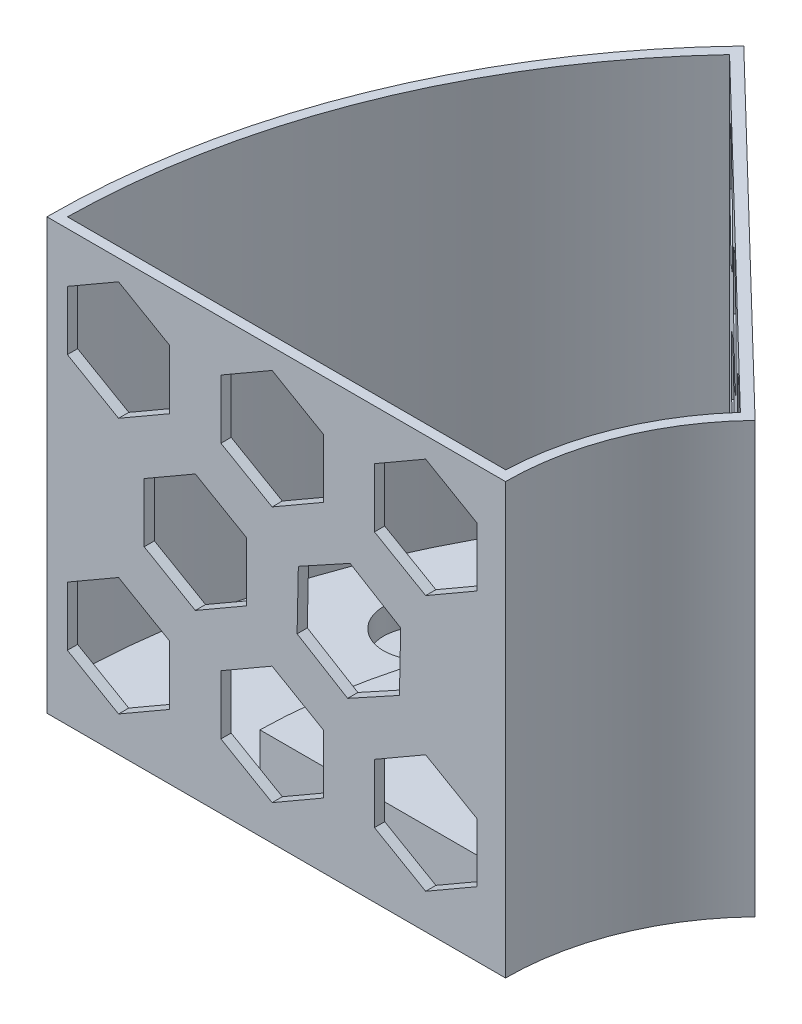
SolidWorks part; units mm, degrees
ref_plane "Alzado" through (0, 0, 0) normal (0, 0, 1) x (1, 0, 0)
ref_plane "Planta" through (0, 0, 0) normal (0, 1, 0) x (1, 0, 0)
ref_plane "Vista lateral" through (0, 0, 0) normal (1, 0, 0) x (0, 0, -1)
sketch "Croquis1" plane through (0, 0, 0) normal (0, 1, 0) x (1, 0, 0)
  line L0 (0, 0) -> (-75, 0) construction
  line L1 (0, 0) -> (-50.2099, 48.4872) construction
  line L2 (-25, 0) -> (-69.8, 0)
  line L4 (-50.2099, 48.4872) -> (-17.9835, 17.3665)
  circle A0 centre (0, 0) radius 75 construction
  circle A1 centre (0, 0) radius 69.8 construction
  circle A2 centre (0, 0) radius 25 construction
  arc A3 (-25, 0) -> (-17.9835, 17.3665) centre (0, 0) cw
  arc A4 (-69.8, 0) -> (-50.2099, 48.4872) centre (0, 0) cw
  dimension "D1" = 150
  dimension "D2" = 5.2
  dimension "D3" = 50
  dimension "D4" = 44
extrude "Saliente-Extruir1" add sketch "Croquis1" along normal blind 40
shell "Vaciado1" thickness 1
sketch "Croquis4" plane through (0, 0, 0) normal (0, -1, 0) x (1, 0, 0)
  line L0 (-25, 0) -> (-69.8, 0)
  line L1 (-17.9835, -17.3665) -> (-50.2099, -48.4872)
  arc A0 (-69.8, 0) -> (-50.2099, -48.4872) centre (0, 0) ccw
  arc A1 (-25, 0) -> (-17.9835, -17.3665) centre (0, 0) ccw
extrude "Saliente-Extruir3" add sketch "Croquis4" along normal blind 2
sketch "Croquis5" plane through (0, 1, 0) normal (0, 1, 0) x (1, 0, 0)
  line L0 (0, 0) -> (-64.7174, 26.1475) construction
  arc A1 (-50.2099, 48.4872) -> (-69.8, 0) centre (0, 0) ccw construction
  circle A2 centre (-55.631, 22.4764) radius 3.75
  dimension "D1" = 7.5
  dimension "D2" = 60
extrude "Cortar-Extruir2" cut sketch "Croquis5" against normal blind 2.5
sketch "Croquis6" plane through (0, 1, 0) normal (0, 1, 0) x (1, 0, 0)
  line L1 (-25, 0) -> (-50, 0)
  line L3 (-17.9835, 17.3665) -> (-35.967, 34.7329)
  line L4 (-17.9835, 17.3665) -> (-50.2099, 48.4872) construction
  circle A0 centre (0, 0) radius 50 construction
  arc A1 (-25, 0) -> (-17.9835, 17.3665) centre (0, 0) cw
  arc A3 (-50, 0) -> (-35.967, 34.7329) centre (0, 0) cw
  dimension "D1" = 100
extrude "Saliente-Extruir5" add sketch "Croquis6" along normal blind 5
sketch "Croquis2" plane through (0, -2, 0) normal (0, 1, 0) x (1, 0, 0)
  line L0 (-39.7289, 27.8185) -> (-29.899, 20.9355)
  line L1 (-47.9029, 7.5871) -> (-36.0506, 5.7099)
  line L2 (-17.9835, 17.3665) -> (-50.2099, 48.4872) construction
  circle A0 centre (0, 0) radius 36.5 construction
  circle A1 centre (0, 0) radius 48.5 construction
  arc A2 (-36.0506, 5.7099) -> (-29.899, 20.9355) centre (0, 0) cw
  arc A3 (-47.9029, 7.5871) -> (-39.7289, 27.8185) centre (0, 0) cw
  dimension "D1" = 73
  dimension "D2" = 97
  dimension "D3" = 9
  dimension "D4" = 26
extrude "Cortar-Extruir3" cut sketch "Croquis2" along normal blind 6
sketch "Croquis7" plane through (0, 0, 0) normal (0, 0, 1) x (1, 0, 0)
  line L0 (-69.8, 40) -> (-69.8, -2) construction
  line L1 (-62.8, 38) -> (-67.8, 35.1132)
  line L2 (-67.8, 35.1132) -> (-67.8, 29.3397)
  line L3 (-67.8, 29.3397) -> (-62.8, 26.453)
  line L4 (-62.8, 26.453) -> (-57.8, 29.3397)
  line L5 (-57.8, 29.3397) -> (-57.8, 35.1132)
  line L6 (-57.8, 35.1132) -> (-62.8, 38)
  line L7 (-69.8, 40) -> (-25, 40) construction
  line L8 (-47.8, 38) -> (-52.8, 35.1132)
  line L9 (-52.8, 35.1132) -> (-52.8, 29.3397)
  line L10 (-52.8, 29.3397) -> (-47.8, 26.453)
  line L11 (-47.8, 26.453) -> (-42.8, 29.3397)
  line L12 (-42.8, 29.3397) -> (-42.8, 35.1132)
  line L13 (-42.8, 35.1132) -> (-47.8, 38)
  line L14 (-32.8, 38) -> (-37.8, 35.1132)
  line L15 (-37.8, 35.1132) -> (-37.8, 29.3397)
  line L16 (-37.8, 29.3397) -> (-32.8, 26.453)
  line L17 (-32.8, 26.453) -> (-27.8, 29.3397)
  line L18 (-27.8, 29.3397) -> (-27.8, 35.1132)
  line L19 (-27.8, 35.1132) -> (-32.8, 38)
  line L20 (-47.8, 12.9837) -> (-52.8, 10.097)
  line L21 (-52.8, 10.097) -> (-52.8, 4.3235)
  line L22 (-52.8, 4.3235) -> (-47.8, 1.4367)
  line L23 (-47.8, 1.4367) -> (-42.8, 4.3235)
  line L24 (-42.8, 4.3235) -> (-42.8, 10.097)
  line L25 (-42.8, 10.097) -> (-47.8, 12.9837)
  line L26 (-32.8, 12.9837) -> (-37.8, 10.097)
  line L27 (-37.8, 10.097) -> (-37.8, 4.3235)
  line L28 (-37.8, 4.3235) -> (-32.8, 1.4367)
  line L29 (-32.8, 1.4367) -> (-27.8, 4.3235)
  line L30 (-27.8, 4.3235) -> (-27.8, 10.097)
  line L31 (-27.8, 10.097) -> (-32.8, 12.9837)
  line L32 (-62.8, 12.9837) -> (-67.8, 10.097)
  line L33 (-67.8, 10.097) -> (-67.8, 4.3235)
  line L34 (-67.8, 4.3235) -> (-62.8, 1.4367)
  line L35 (-62.8, 1.4367) -> (-57.8, 4.3235)
  line L36 (-57.8, 4.3235) -> (-57.8, 10.097)
  line L37 (-57.8, 10.097) -> (-62.8, 12.9837)
  line L38 (-57.8, 29.3397) -> (-52.8, 29.3397) construction
  line L39 (-55.2993, 25.4919) -> (-60.2997, 22.6057)
  line L40 (-60.2997, 22.6057) -> (-60.3003, 16.8322)
  line L41 (-60.3003, 16.8322) -> (-55.3007, 13.9449)
  line L42 (-55.3007, 13.9449) -> (-50.3003, 16.831)
  line L43 (-50.3003, 16.831) -> (-50.2997, 22.6045)
  line L44 (-50.2997, 22.6045) -> (-55.2993, 25.4919)
  line L45 (-40.1778, 25.4906) -> (-45.2378, 22.7103)
  line L46 (-45.2378, 22.7103) -> (-45.36, 16.9381)
  line L47 (-45.36, 16.9381) -> (-40.4222, 13.9462)
  line L48 (-40.4222, 13.9462) -> (-35.3622, 16.7264)
  line L49 (-35.3622, 16.7264) -> (-35.24, 22.4986)
  line L50 (-35.24, 22.4986) -> (-40.1778, 25.4906)
  line L51 (-42.8, 29.3397) -> (-37.8, 29.3397) construction
  line L52 (-62.8, 26.453) -> (-62.8, 12.9837) construction
  circle A0 centre (-62.8, 32.2265) radius 5 construction
  circle A1 centre (-55.3, 19.7184) radius 5 construction
  circle A2 centre (-40.3, 19.7184) radius 5 construction
  point P51 (-55.3, 29.3397)
  point P59 (-40.3, 29.3397)
  point P60 (-62.8, 19.7184)
  dimension "D2" = 10
  dimension "D1" = 2
  dimension "D3" = 2
  dimension "D4" = 3
  dimension "D5" = 2
extrude "Cortar-Extruir4" cut sketch "Croquis7" against normal blind 1
sketch "Croquis8" plane through (0, 0, 0) normal (-0.6947, 0, 0.7193) x (0.7193, 0, 0.6947)
  line L1 (-62.8, 38) -> (-67.8, 35.1132)
  line L2 (-67.8, 35.1132) -> (-67.8, 29.3397)
  line L3 (-67.8, 29.3397) -> (-62.8, 26.453)
  line L4 (-62.8, 26.453) -> (-57.8, 29.3397)
  line L5 (-57.8, 29.3397) -> (-57.8, 35.1132)
  line L6 (-57.8, 35.1132) -> (-62.8, 38)
  line L8 (-47.8, 38) -> (-52.8, 35.1132)
  line L9 (-52.8, 35.1132) -> (-52.8, 29.3397)
  line L10 (-52.8, 29.3397) -> (-47.8, 26.453)
  line L11 (-47.8, 26.453) -> (-42.8, 29.3397)
  line L12 (-42.8, 29.3397) -> (-42.8, 35.1132)
  line L13 (-42.8, 35.1132) -> (-47.8, 38)
  line L14 (-32.8, 38) -> (-37.8, 35.1132)
  line L15 (-37.8, 35.1132) -> (-37.8, 29.3397)
  line L16 (-37.8, 29.3397) -> (-32.8, 26.453)
  line L17 (-32.8, 26.453) -> (-27.8, 29.3397)
  line L18 (-27.8, 29.3397) -> (-27.8, 35.1132)
  line L19 (-27.8, 35.1132) -> (-32.8, 38)
  line L20 (-47.8, 12.9837) -> (-52.8, 10.097)
  line L21 (-52.8, 10.097) -> (-52.8, 4.3235)
  line L22 (-52.8, 4.3235) -> (-47.8, 1.4367)
  line L23 (-47.8, 1.4367) -> (-42.8, 4.3235)
  line L24 (-42.8, 4.3235) -> (-42.8, 10.097)
  line L25 (-42.8, 10.097) -> (-47.8, 12.9837)
  line L26 (-32.8, 12.9837) -> (-37.8, 10.097)
  line L27 (-37.8, 10.097) -> (-37.8, 4.3235)
  line L28 (-37.8, 4.3235) -> (-32.8, 1.4367)
  line L29 (-32.8, 1.4367) -> (-27.8, 4.3235)
  line L30 (-27.8, 4.3235) -> (-27.8, 10.097)
  line L31 (-27.8, 10.097) -> (-32.8, 12.9837)
  line L32 (-62.8, 12.9837) -> (-67.8, 10.097)
  line L33 (-67.8, 10.097) -> (-67.8, 4.3235)
  line L34 (-67.8, 4.3235) -> (-62.8, 1.4367)
  line L35 (-62.8, 1.4367) -> (-57.8, 4.3235)
  line L36 (-57.8, 4.3235) -> (-57.8, 10.097)
  line L37 (-57.8, 10.097) -> (-62.8, 12.9837)
  line L38 (-57.8, 29.3397) -> (-52.8, 29.3397) construction
  line L39 (-55.2993, 25.4919) -> (-60.2997, 22.6057)
  line L40 (-60.2997, 22.6057) -> (-60.3003, 16.8322)
  line L41 (-60.3003, 16.8322) -> (-55.3007, 13.9449)
  line L42 (-55.3007, 13.9449) -> (-50.3003, 16.831)
  line L43 (-50.3003, 16.831) -> (-50.2997, 22.6045)
  line L44 (-50.2997, 22.6045) -> (-55.2993, 25.4919)
  line L45 (-40.1778, 25.4906) -> (-45.2378, 22.7103)
  line L46 (-45.2378, 22.7103) -> (-45.36, 16.9381)
  line L47 (-45.36, 16.9381) -> (-40.4222, 13.9462)
  line L48 (-40.4222, 13.9462) -> (-35.3622, 16.7264)
  line L49 (-35.3622, 16.7264) -> (-35.24, 22.4986)
  line L50 (-35.24, 22.4986) -> (-40.1778, 25.4906)
  line L51 (-42.8, 29.3397) -> (-37.8, 29.3397) construction
  line L52 (-62.8, 26.453) -> (-62.8, 12.9837) construction
  circle A0 centre (-62.8, 32.2265) radius 5 construction
  circle A1 centre (-55.3, 19.7184) radius 5 construction
  circle A2 centre (-40.3, 19.7184) radius 5 construction
  point P51 (-55.3, 29.3397)
  point P59 (-40.3, 29.3397)
  point P60 (-62.8, 19.7184)
  dimension "D2" = 10
  dimension "D4" = 3
  dimension "D5" = 2
extrude "Cortar-Extruir5" cut sketch "Croquis8" along normal blind 1
